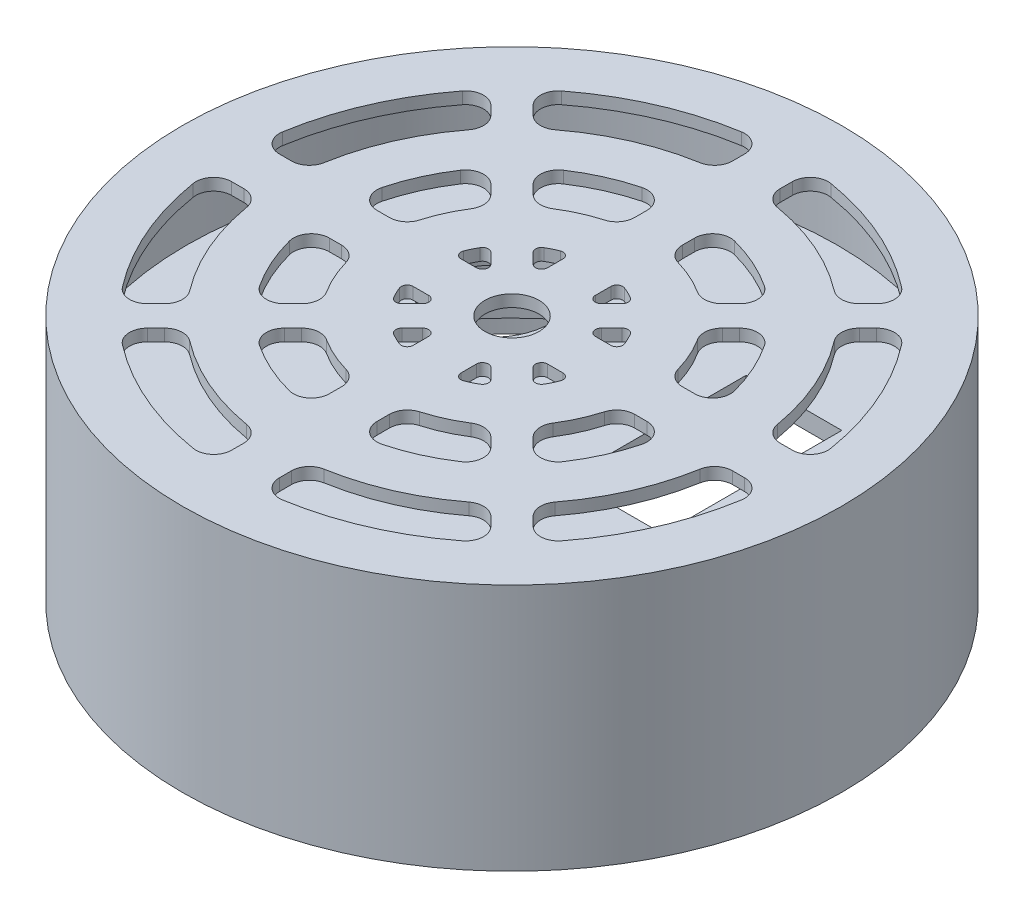
SolidWorks part; units mm, degrees
ref_plane "Front Plane" through (0, 0, 0) normal (0, 0, 1) x (1, 0, 0)
ref_plane "Top Plane" through (0, 0, 0) normal (0, 1, 0) x (1, 0, 0)
ref_plane "Right Plane" through (0, 0, 0) normal (1, 0, 0) x (0, 0, -1)
sketch "Sketch1" plane through (0, 0, 0) normal (0, 1, 0) x (1, 0, 0)
  circle A1 centre (0, 0) radius 55.2
  dimension "D2" = 110.4
extrude "Boss-Extrude1" add sketch "Sketch1" along normal blind 3
sketch "Sketch2" plane through (0, 3, 0) normal (0, 1, 0) x (1, 0, 0)
  circle A0 centre (0, 0) radius 55
  dimension "D1" = 110
extrude "Cut-Extrude1" cut sketch "Sketch2" against normal through all
sketch "Sketch4" plane through (0, 3, 0) normal (0, 1, 0) x (1, 0, 0)
  line L0 (0, 0) -> (8.2385, 0) construction
  line L1 (8.2385, 0) -> (0, 0) construction
  line L2 (0, 0) -> (0, 11.6273) construction
  line L3 (-45.2, -5) -> (-45.2, 5)
  line L4 (-45.2, -5) -> (-53.768, -5)
  line L5 (-45.2, 5) -> (-53.768, 5)
  circle A1 centre (0, 0) radius 55.2
  circle A2 centre (0, 0) radius 55.2
  arc A3 (-53.768, -5) -> (-53.768, 5) centre (0, 0) ccw
  point P12 (-45.2, 0)
  dimension "D2" = 110.4
  dimension "D3" = 108
  dimension "D4" = 10
  dimension "D5" = 10
  dimension "D1" = 0
extrude "Boss-Extrude2" add sketch "Sketch4" along normal blind 18.5
sketch "Sketch8" plane through (0, 3, 0) normal (0, -1, 0) x (1, 0, 0)
  line L2 (-53.768, -5) -> (-45.2, -5) construction
  line L3 (-45.2, 5) -> (-54.7723, 5)
  line L4 (-45.2, 5) -> (-45.2, -5)
  line L5 (-45.2, -5) -> (-54.7723, -5)
  circle A2 centre (0, 0) radius 55 construction
  arc A3 (-54.7723, 5) -> (-54.7723, -5) centre (0, 0) ccw
extrude "Boss-Extrude4" add sketch "Sketch8" along normal blind 3
sketch "Sketch6" plane through (0, 21.5, 0) normal (0, 1, 0) x (1, 0, 0)
  line L1 (11.2131, 28) -> (27.2131, 28)
  line L2 (11.2131, 28) -> (11.2131, -2)
  line L3 (11.2131, -2) -> (27.2131, -2)
  line L4 (27.2131, 28) -> (27.2131, -2)
  line L5 (11.2131, 28) -> (27.2131, -2) construction
  line L6 (11.2131, -2) -> (27.2131, 28) construction
  line L7 (12.1174, 28) -> (26.3174, 28) construction
  circle A0 centre (0, 0) radius 55.2
  circle A1 centre (-22.2011, 19.0599) radius 9.5
  point P5 (19.2131, 13)
  point P10 (0, 0)
  point P11 (0, 0)
  point P14 (0, 0)
  point P16 (0, 0)
  dimension "D1" = 19
  dimension "D2" = 30
  dimension "D3" = 16
  dimension "D6" = 110.4
  dimension "D4" = 19.2131
  dimension "D5" = 13
  dimension "D7" = 19.0599
  dimension "D8" = 22.2011
extrude "Boss-Extrude3" add sketch "Sketch6" along normal blind 3
sketch "Sketch9" plane through (0, 24.5, 0) normal (0, 1, 0) x (1, 0, 0)
  circle A0 centre (0, 0) radius 55.2
  circle A1 centre (0, 0) radius 54.5
  dimension "D1" = 110.4
  dimension "D2" = 109
extrude "Boss-Extrude5" add sketch "Sketch9" along normal blind 15
sketch "Sketch10" plane through (0, 39.5, 0) normal (0, 1, 0) x (1, 0, 0)
  line L0 (0, 0) -> (18.0348, 0) construction
  line L2 (0, 0) -> (0, 14.913) construction
  line L5 (0, 0) -> (-39.0323, 39.0323) construction
  line L10 (-4, 40.9054) -> (-4, 42.9331)
  line L11 (-4, 24.5204) -> (-4, 26.5942)
  line L12 (-4, 9.9497) -> (-4, 12.5399)
  line L14 (-12.5399, 4) -> (-9.9497, 4)
  line L15 (-26.5942, 4) -> (-24.5204, 4)
  line L16 (-42.9331, 4) -> (-40.9054, 4)
  line L21 (-27.3183, 30.8538) -> (-28.7445, 32.2801)
  line L22 (-30.8538, 27.3183) -> (-32.2801, 28.7445)
  line L23 (-15.839, 19.3746) -> (-17.2848, 20.8203)
  line L24 (-19.3746, 15.839) -> (-20.8203, 17.2848)
  line L25 (-5.7071, 9.2426) -> (-7.4518, 10.9873)
  line L26 (-9.2426, 5.7071) -> (-10.9873, 7.4518)
  line L51 (9.2426, 5.7071) -> (10.9873, 7.4518)
  line L52 (12.5399, 4) -> (9.9497, 4)
  line L53 (5.7071, 9.2426) -> (7.4518, 10.9873)
  line L54 (4, 9.9497) -> (4, 12.5399)
  line L55 (4, 24.5204) -> (4, 26.5942)
  line L56 (15.839, 19.3746) -> (17.2848, 20.8203)
  line L57 (19.3746, 15.839) -> (20.8203, 17.2848)
  line L58 (26.5942, 4) -> (24.5204, 4)
  line L59 (42.9331, 4) -> (40.9054, 4)
  line L60 (30.8538, 27.3183) -> (32.2801, 28.7445)
  line L61 (4, 40.9054) -> (4, 42.9331)
  line L62 (27.3183, 30.8538) -> (28.7445, 32.2801)
  line L63 (30.8538, -27.3183) -> (32.2801, -28.7445)
  line L64 (42.9331, -4) -> (40.9054, -4)
  line L65 (26.5942, -4) -> (24.5204, -4)
  line L66 (19.3746, -15.839) -> (20.8203, -17.2848)
  line L67 (9.2426, -5.7071) -> (10.9873, -7.4518)
  line L68 (12.5399, -4) -> (9.9497, -4)
  line L69 (-9.2426, -5.7071) -> (-10.9873, -7.4518)
  line L70 (-12.5399, -4) -> (-9.9497, -4)
  line L71 (-5.7071, -9.2426) -> (-7.4518, -10.9873)
  line L72 (-4, -9.9497) -> (-4, -12.5399)
  line L73 (4, -9.9497) -> (4, -12.5399)
  line L74 (5.7071, -9.2426) -> (7.4518, -10.9873)
  line L75 (4, -24.5204) -> (4, -26.5942)
  line L76 (15.839, -19.3746) -> (17.2848, -20.8203)
  line L77 (4, -40.9054) -> (4, -42.9331)
  line L78 (27.3183, -30.8538) -> (28.7445, -32.2801)
  line L79 (-4, -24.5204) -> (-4, -26.5942)
  line L80 (-15.839, -19.3746) -> (-17.2848, -20.8203)
  line L81 (-19.3746, -15.839) -> (-20.8203, -17.2848)
  line L82 (-26.5942, -4) -> (-24.5204, -4)
  line L83 (-42.9331, -4) -> (-40.9054, -4)
  line L84 (-30.8538, -27.3183) -> (-32.2801, -28.7445)
  line L85 (-4, -40.9054) -> (-4, -42.9331)
  line L86 (-27.3183, -30.8538) -> (-28.7445, -32.2801)
  circle A0 centre (0, 0) radius 55.2
  arc A1 (-36.7739, 28.4593) -> (-45.894, 7.4828) centre (0, 0) ccw
  circle A2 centre (0, 0) radius 54.5 construction
  arc A3 (-30.5914, 23.3755) -> (-37.9484, 6.494) centre (0, 0) ccw
  circle A7 centre (0, 0) radius 4.5314
  arc A10 (-25.4444, 16.8177) -> (-29.4954, 7.7636) centre (0, 0) ccw
  arc A11 (-18.967, 12.1039) -> (-21.6356, 6.1765) centre (0, 0) ccw
  arc A12 (-7.4828, 45.894) -> (-28.4593, 36.7739) centre (0, 0) ccw
  arc A13 (-6.494, 37.9484) -> (-23.3755, 30.5914) centre (0, 0) ccw
  arc A14 (-7.7636, 29.4954) -> (-16.8177, 25.4444) centre (0, 0) ccw
  arc A15 (-6.1765, 21.6356) -> (-12.1039, 18.967) centre (0, 0) ccw
  arc A16 (-5.3704, 13.4688) -> (-7.2443, 12.5607) centre (0, 0) ccw
  arc A17 (-12.5607, 7.2443) -> (-13.4688, 5.3704) centre (0, 0) ccw
  arc A46 (-4, 24.5204) -> (-6.1765, 21.6356) centre (-7, 24.5204) cw
  arc A47 (-15.839, 19.3746) -> (-12.1039, 18.967) centre (-13.7177, 21.4959) ccw
  arc A48 (-16.8177, 25.4444) -> (-17.2848, 20.8203) centre (-15.1635, 22.9416) ccw
  arc A49 (-7.7636, 29.4954) -> (-4, 26.5942) centre (-7, 26.5942) cw
  arc A50 (-4, 40.9054) -> (-6.494, 37.9484) centre (-7, 40.9054) cw
  arc A51 (-7.4828, 45.894) -> (-4, 42.9331) centre (-7, 42.9331) cw
  arc A52 (-28.4593, 36.7739) -> (-28.7445, 32.2801) centre (-26.6232, 34.4014) ccw
  arc A53 (-27.3183, 30.8538) -> (-23.3755, 30.5914) centre (-25.197, 32.9752) ccw
  arc A54 (-25.4444, 16.8177) -> (-20.8203, 17.2848) centre (-22.9416, 15.1635) cw
  arc A55 (-19.3746, 15.839) -> (-18.967, 12.1039) centre (-21.4959, 13.7177) cw
  arc A56 (-21.6356, 6.1765) -> (-24.5204, 4) centre (-24.5204, 7) cw
  arc A57 (-26.5942, 4) -> (-29.4954, 7.7636) centre (-26.5942, 7) cw
  arc A58 (-37.9484, 6.494) -> (-40.9054, 4) centre (-40.9054, 7) cw
  arc A59 (-30.8538, 27.3183) -> (-30.5914, 23.3755) centre (-32.9752, 25.197) cw
  arc A60 (-42.9331, 4) -> (-45.894, 7.4828) centre (-42.9331, 7) cw
  arc A61 (-36.7739, 28.4593) -> (-32.2801, 28.7445) centre (-34.4014, 26.6232) cw
  arc A62 (-5.7071, 9.2426) -> (-4, 9.9497) centre (-5, 9.9497) ccw
  arc A63 (-9.2426, 5.7071) -> (-9.9497, 4) centre (-9.9497, 5) cw
  arc A64 (-12.5607, 7.2443) -> (-10.9873, 7.4518) centre (-11.6944, 6.7447) cw
  arc A65 (-12.5399, 4) -> (-13.4688, 5.3704) centre (-12.5399, 5) cw
  arc A66 (-7.2443, 12.5607) -> (-7.4518, 10.9873) centre (-6.7447, 11.6944) ccw
  arc A67 (-5.3704, 13.4688) -> (-4, 12.5399) centre (-5, 12.5399) cw
  arc A68 (12.5607, 7.2443) -> (13.4688, 5.3704) centre (0, 0) cw
  arc A69 (12.5607, 7.2443) -> (10.9873, 7.4518) centre (11.6944, 6.7447) ccw
  arc A70 (9.2426, 5.7071) -> (9.9497, 4) centre (9.9497, 5) ccw
  arc A71 (12.5399, 4) -> (13.4688, 5.3704) centre (12.5399, 5) ccw
  arc A72 (7.2443, 12.5607) -> (7.4518, 10.9873) centre (6.7447, 11.6944) cw
  arc A73 (5.3704, 13.4688) -> (7.2443, 12.5607) centre (0, 0) cw
  arc A74 (5.7071, 9.2426) -> (4, 9.9497) centre (5, 9.9497) cw
  arc A75 (5.3704, 13.4688) -> (4, 12.5399) centre (5, 12.5399) ccw
  arc A76 (6.1765, 21.6356) -> (12.1039, 18.967) centre (0, 0) cw
  arc A77 (4, 24.5204) -> (6.1765, 21.6356) centre (7, 24.5204) ccw
  arc A78 (7.7636, 29.4954) -> (4, 26.5942) centre (7, 26.5942) ccw
  arc A79 (7.7636, 29.4954) -> (16.8177, 25.4444) centre (0, 0) cw
  arc A80 (15.839, 19.3746) -> (12.1039, 18.967) centre (13.7177, 21.4959) cw
  arc A81 (16.8177, 25.4444) -> (17.2848, 20.8203) centre (15.1635, 22.9416) cw
  arc A82 (25.4444, 16.8177) -> (20.8203, 17.2848) centre (22.9416, 15.1635) ccw
  arc A83 (25.4444, 16.8177) -> (29.4954, 7.7636) centre (0, 0) cw
  arc A84 (26.5942, 4) -> (29.4954, 7.7636) centre (26.5942, 7) ccw
  arc A85 (19.3746, 15.839) -> (18.967, 12.1039) centre (21.4959, 13.7177) ccw
  arc A86 (21.6356, 6.1765) -> (24.5204, 4) centre (24.5204, 7) ccw
  arc A87 (18.967, 12.1039) -> (21.6356, 6.1765) centre (0, 0) cw
  arc A88 (30.5914, 23.3755) -> (37.9484, 6.494) centre (0, 0) cw
  arc A89 (37.9484, 6.494) -> (40.9054, 4) centre (40.9054, 7) ccw
  arc A90 (42.9331, 4) -> (45.894, 7.4828) centre (42.9331, 7) ccw
  arc A91 (36.7739, 28.4593) -> (45.894, 7.4828) centre (0, 0) cw
  arc A92 (30.8538, 27.3183) -> (30.5914, 23.3755) centre (32.9752, 25.197) ccw
  arc A93 (36.7739, 28.4593) -> (32.2801, 28.7445) centre (34.4014, 26.6232) ccw
  arc A94 (6.494, 37.9484) -> (23.3755, 30.5914) centre (0, 0) cw
  arc A95 (4, 40.9054) -> (6.494, 37.9484) centre (7, 40.9054) ccw
  arc A96 (7.4828, 45.894) -> (4, 42.9331) centre (7, 42.9331) ccw
  arc A97 (7.4828, 45.894) -> (28.4593, 36.7739) centre (0, 0) cw
  arc A98 (28.4593, 36.7739) -> (28.7445, 32.2801) centre (26.6232, 34.4014) cw
  arc A99 (27.3183, 30.8538) -> (23.3755, 30.5914) centre (25.197, 32.9752) cw
  arc A100 (30.8538, -27.3183) -> (30.5914, -23.3755) centre (32.9752, -25.197) cw
  arc A101 (36.7739, -28.4593) -> (32.2801, -28.7445) centre (34.4014, -26.6232) cw
  arc A102 (36.7739, -28.4593) -> (45.894, -7.4828) centre (0, 0) ccw
  arc A103 (42.9331, -4) -> (45.894, -7.4828) centre (42.9331, -7) cw
  arc A104 (37.9484, -6.494) -> (40.9054, -4) centre (40.9054, -7) cw
  arc A105 (30.5914, -23.3755) -> (37.9484, -6.494) centre (0, 0) ccw
  arc A106 (19.3746, -15.839) -> (18.967, -12.1039) centre (21.4959, -13.7177) cw
  arc A107 (18.967, -12.1039) -> (21.6356, -6.1765) centre (0, 0) ccw
  arc A108 (21.6356, -6.1765) -> (24.5204, -4) centre (24.5204, -7) cw
  arc A109 (26.5942, -4) -> (29.4954, -7.7636) centre (26.5942, -7) cw
  arc A110 (25.4444, -16.8177) -> (29.4954, -7.7636) centre (0, 0) ccw
  arc A111 (25.4444, -16.8177) -> (20.8203, -17.2848) centre (22.9416, -15.1635) cw
  arc A112 (12.5607, -7.2443) -> (10.9873, -7.4518) centre (11.6944, -6.7447) cw
  arc A113 (9.2426, -5.7071) -> (9.9497, -4) centre (9.9497, -5) cw
  arc A114 (12.5399, -4) -> (13.4688, -5.3704) centre (12.5399, -5) cw
  arc A115 (12.5607, -7.2443) -> (13.4688, -5.3704) centre (0, 0) ccw
  arc A116 (-12.5607, -7.2443) -> (-13.4688, -5.3704) centre (0, 0) cw
  arc A117 (-12.5607, -7.2443) -> (-10.9873, -7.4518) centre (-11.6944, -6.7447) ccw
  arc A118 (-9.2426, -5.7071) -> (-9.9497, -4) centre (-9.9497, -5) ccw
  arc A119 (-12.5399, -4) -> (-13.4688, -5.3704) centre (-12.5399, -5) ccw
  arc A120 (-7.2443, -12.5607) -> (-7.4518, -10.9873) centre (-6.7447, -11.6944) cw
  arc A121 (-5.3704, -13.4688) -> (-7.2443, -12.5607) centre (0, 0) cw
  arc A122 (-5.7071, -9.2426) -> (-4, -9.9497) centre (-5, -9.9497) cw
  arc A123 (-5.3704, -13.4688) -> (-4, -12.5399) centre (-5, -12.5399) ccw
  arc A124 (5.7071, -9.2426) -> (4, -9.9497) centre (5, -9.9497) ccw
  arc A125 (5.3704, -13.4688) -> (4, -12.5399) centre (5, -12.5399) cw
  arc A126 (5.3704, -13.4688) -> (7.2443, -12.5607) centre (0, 0) ccw
  arc A127 (7.2443, -12.5607) -> (7.4518, -10.9873) centre (6.7447, -11.6944) ccw
  arc A128 (4, -24.5204) -> (6.1765, -21.6356) centre (7, -24.5204) cw
  arc A129 (7.7636, -29.4954) -> (4, -26.5942) centre (7, -26.5942) cw
  arc A130 (7.7636, -29.4954) -> (16.8177, -25.4444) centre (0, 0) ccw
  arc A131 (16.8177, -25.4444) -> (17.2848, -20.8203) centre (15.1635, -22.9416) ccw
  arc A132 (15.839, -19.3746) -> (12.1039, -18.967) centre (13.7177, -21.4959) ccw
  arc A133 (6.1765, -21.6356) -> (12.1039, -18.967) centre (0, 0) ccw
  arc A134 (4, -40.9054) -> (6.494, -37.9484) centre (7, -40.9054) cw
  arc A135 (7.4828, -45.894) -> (4, -42.9331) centre (7, -42.9331) cw
  arc A136 (7.4828, -45.894) -> (28.4593, -36.7739) centre (0, 0) ccw
  arc A137 (28.4593, -36.7739) -> (28.7445, -32.2801) centre (26.6232, -34.4014) ccw
  arc A138 (27.3183, -30.8538) -> (23.3755, -30.5914) centre (25.197, -32.9752) ccw
  arc A139 (6.494, -37.9484) -> (23.3755, -30.5914) centre (0, 0) ccw
  arc A140 (-6.1765, -21.6356) -> (-12.1039, -18.967) centre (0, 0) cw
  arc A141 (-4, -24.5204) -> (-6.1765, -21.6356) centre (-7, -24.5204) ccw
  arc A142 (-7.7636, -29.4954) -> (-4, -26.5942) centre (-7, -26.5942) ccw
  arc A143 (-7.7636, -29.4954) -> (-16.8177, -25.4444) centre (0, 0) cw
  arc A144 (-15.839, -19.3746) -> (-12.1039, -18.967) centre (-13.7177, -21.4959) cw
  arc A145 (-16.8177, -25.4444) -> (-17.2848, -20.8203) centre (-15.1635, -22.9416) cw
  arc A146 (-25.4444, -16.8177) -> (-20.8203, -17.2848) centre (-22.9416, -15.1635) ccw
  arc A147 (-25.4444, -16.8177) -> (-29.4954, -7.7636) centre (0, 0) cw
  arc A148 (-26.5942, -4) -> (-29.4954, -7.7636) centre (-26.5942, -7) ccw
  arc A149 (-19.3746, -15.839) -> (-18.967, -12.1039) centre (-21.4959, -13.7177) ccw
  arc A150 (-21.6356, -6.1765) -> (-24.5204, -4) centre (-24.5204, -7) ccw
  arc A151 (-18.967, -12.1039) -> (-21.6356, -6.1765) centre (0, 0) cw
  arc A152 (-30.5914, -23.3755) -> (-37.9484, -6.494) centre (0, 0) cw
  arc A153 (-37.9484, -6.494) -> (-40.9054, -4) centre (-40.9054, -7) ccw
  arc A154 (-42.9331, -4) -> (-45.894, -7.4828) centre (-42.9331, -7) ccw
  arc A155 (-36.7739, -28.4593) -> (-45.894, -7.4828) centre (0, 0) cw
  arc A156 (-30.8538, -27.3183) -> (-30.5914, -23.3755) centre (-32.9752, -25.197) ccw
  arc A157 (-36.7739, -28.4593) -> (-32.2801, -28.7445) centre (-34.4014, -26.6232) ccw
  arc A158 (-6.494, -37.9484) -> (-23.3755, -30.5914) centre (0, 0) cw
  arc A159 (-4, -40.9054) -> (-6.494, -37.9484) centre (-7, -40.9054) ccw
  arc A160 (-7.4828, -45.894) -> (-4, -42.9331) centre (-7, -42.9331) ccw
  arc A161 (-7.4828, -45.894) -> (-28.4593, -36.7739) centre (0, 0) cw
  arc A162 (-28.4593, -36.7739) -> (-28.7445, -32.2801) centre (-26.6232, -34.4014) cw
  arc A163 (-27.3183, -30.8538) -> (-23.3755, -30.5914) centre (-25.197, -32.9752) cw
  point P3 (0, 0)
  point P7 (0, 0)
  point P18 (0, 0)
  point P24 (-4, 30.2366)
  point P29 (-4, 38.2916)
  point P34 (-4, 46.3276)
  point P73 (-4, 7.5355)
  dimension "D1" = 110.4
  dimension "D2" = 8
  dimension "D3" = 8
  dimension "D4" = 8.0551
  dimension "D5" = 8
  dimension "D6" = 4
  dimension "D7" = 8
  dimension "D9" = 8
  dimension "D11" = 2.5
  dimension "D14" = 4
  dimension "D12" = 5.9686
  dimension "D13" = 3
  dimension "D16" = 1
  dimension "D8" = 45
  dimension "D10" = 2.5
  dimension "D15" = 4
extrude "Boss-Extrude6" add sketch "Sketch10" along normal blind 2
